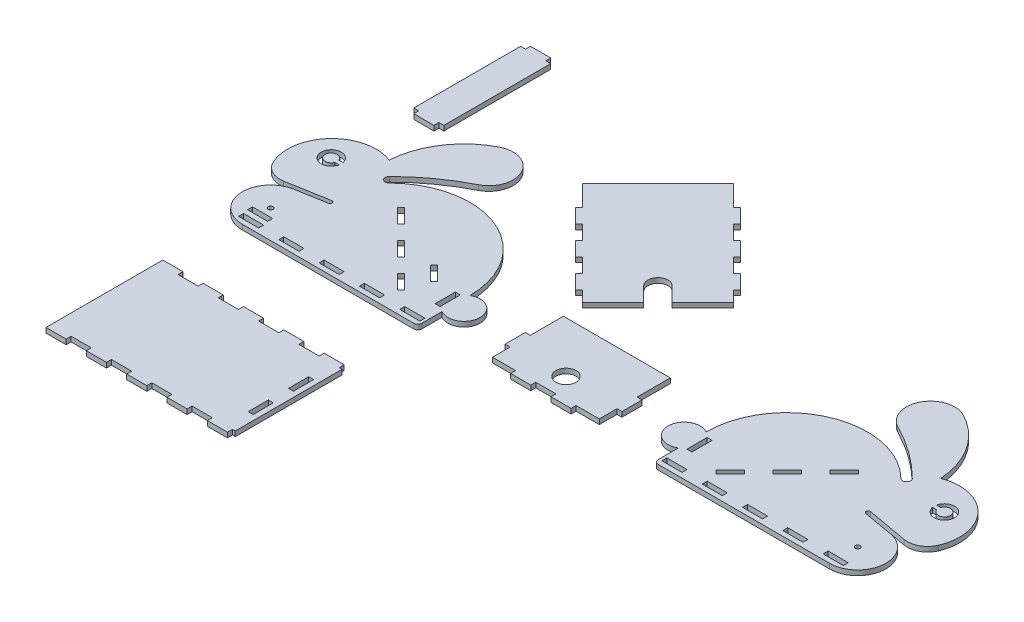
SolidWorks part; units mm, degrees
ref_plane "Front Plane" through (0, 0, 0) normal (0, 0, 1) x (1, 0, 0)
ref_plane "Top Plane" through (0, 0, 0) normal (0, 1, 0) x (1, 0, 0)
ref_plane "Right Plane" through (0, 0, 0) normal (1, 0, 0) x (0, 0, -1)
sketch "Sketch1" plane through (0, 0, 0) normal (0, 1, 0) x (1, 0, 0)
  line L0 (57.15, -63.5) -> (57.15, 63.5) construction
  line L1 (-76.2, 63.5) -> (76.2, 63.5) construction
  line L2 (-76.2, 63.5) -> (-76.2, -63.5) construction
  line L3 (-76.2, -63.5) -> (76.2, -63.5) construction
  line L4 (76.2, 63.5) -> (76.2, -63.5) construction
  line L5 (-76.2, 63.5) -> (76.2, -63.5) construction
  line L6 (-76.2, -63.5) -> (76.2, 63.5) construction
  point P0 (0, 0)
  dimension "D1" = 152.4
  dimension "D2" = 127
  dimension "D3" = 19.05
sketch "Sketch3" plane through (0, 0, 0) normal (0, 1, 0) x (1, 0, 0)
  line L0 (-76.2, -63.5) -> (76.2, -63.5) construction
  line L1 (-76.2, 63.5) -> (-76.2, -63.5) construction
  circle A0 centre (-50.8, -38.1) radius 25.4 construction
  dimension "D1" = 50.8
sketch "Sketch5" plane through (0, 0, 0) normal (0, 1, 0) x (1, 0, 0)
  line L1 (6.35, -55.88) -> (57.15, -55.88) construction
  line L2 (31.75, -55.88) -> (31.75, -63.5) construction
  line L3 (-76.2, -63.5) -> (76.2, -63.5) construction
  line L4 (57.15, -63.5) -> (57.15, 63.5) construction
  arc A0 (6.35, -55.88) -> (57.15, -55.88) centre (31.75, -17.3567) ccw construction
  dimension "D1" = 7.62
  dimension "D2" = 50.8
sketch "Sketch6" plane through (0, 0, 0) normal (0, 1, 0) x (1, 0, 0)
  line L0 (-50.8, -38.1) -> (-50.8, -55.88) construction
  line L1 (-50.8, -55.88) -> (57.15, -55.88) construction
  line L2 (-53.8875, -20.5901) -> (-35.1269, -17.2821) construction
  line L3 (-35.5679, -14.7807) -> (-35.1269, -17.2821) construction
  line L4 (-53.8875, -20.5901) -> (-35.1269, -20.5901) construction
  line L5 (-35.1269, -20.5901) -> (-35.1269, -17.2821) construction
  line L6 (-35.5679, -14.7807) -> (-61.3497, -19.3267) construction
  line L7 (59.69, -53.34) -> (57.15, -53.34) construction
  line L8 (57.15, -53.34) -> (57.15, -55.88) construction
  line L9 (59.69, -53.34) -> (59.69, -40.64) construction
  line L10 (59.69, -40.64) -> (64.77, -31.8412) construction
  line L11 (64.77, -31.8412) -> (59.69, -23.0424) construction
  line L12 (59.69, -23.0424) -> (59.69, -40.64) construction
  line L13 (-27.031, 12.8787) -> (8.89, -23.0424) construction
  line L14 (8.89, -23.0424) -> (59.69, -23.0424) construction
  line L15 (-27.031, 12.8787) -> (-28.8271, 14.6747) construction
  line L16 (-28.8271, 14.6747) -> (-30.6231, 16.4708) construction
  line L17 (-30.6231, 16.4708) -> (-39.6034, 25.451) construction
  line L18 (-11.8373, 67.2263) -> (-4.9647, 53.6239) construction
  line L19 (-4.9647, 53.6239) -> (1.9078, 40.0215) construction
  line L20 (-75.1597, -11.9793) -> (-49.6295, -0.6281) construction
  line L21 (-49.6295, -0.6281) -> (-39.6034, 25.451) construction
  line L22 (-59.0189, 8.2912) -> (-75.1597, -11.9793) construction
  line L23 (-59.0189, 8.2912) -> (-39.6034, 25.451) construction
  line L26 (-55.4268, 9.5612) -> (-52.7972, 9.5612) construction
  line L27 (-55.4268, 7.0212) -> (-52.7972, 7.0212) construction
  line L28 (-52.7972, 9.5612) -> (-52.7972, 7.0212) construction
  line L29 (-55.4268, 9.5612) -> (-55.4268, 7.0212) construction
  arc A0 (-50.8, -55.88) -> (-53.8875, -20.5901) centre (-50.8, -38.1) cw construction
  arc A1 (-35.1269, -17.2821) -> (-35.5679, -14.7807) centre (-35.3474, -16.0314) ccw construction
  arc A2 (57.15, -55.88) -> (59.69, -53.34) centre (57.15, -53.34) ccw construction
  arc A3 (59.69, -40.64) -> (59.69, -23.0424) centre (64.77, -31.8412) ccw construction
  arc A4 (59.69, -23.0424) -> (-27.031, 12.8787) centre (8.89, -23.0424) ccw construction
  arc A5 (-27.031, 12.8787) -> (-30.6231, 16.4708) centre (-28.8271, 14.6747) cw construction
  arc A6 (-30.6231, 16.4708) -> (1.9078, 40.0215) centre (59.1794, -73.3318) cw construction
  arc A7 (1.9078, 40.0215) -> (-11.8373, 67.2263) centre (-4.9647, 53.6239) ccw construction
  arc A8 (-11.8373, 67.2263) -> (-39.6034, 25.451) centre (11.0713, 21.885) ccw construction
  arc A9 (-61.3497, -19.3267) -> (-75.1597, -11.9793) centre (-63.5551, -6.8197) cw construction
  arc A10 (-75.1597, -11.9793) -> (-39.6034, 25.451) centre (-49.6295, -0.6281) cw construction
  arc A11 (-55.4268, 9.5612) -> (-55.4268, 7.0212) centre (-59.0189, 8.2912) ccw construction
  arc A13 (-52.7972, 9.5612) -> (-52.7972, 7.0212) centre (-59.0189, 8.2912) ccw construction
  dimension "D2" = 1.27
  dimension "D3" = 2.54
  dimension "D5" = 10.16
  dimension "D8" = 2.54
  dimension "D11" = 15.24
  dimension "D12" = 127
  dimension "D13" = 50.8
  dimension "D15" = 12.7
  dimension "D16" = 27.94
  dimension "D18" = 7.62
  dimension "D19" = 2.54
  dimension "D1" = 10
  dimension "D4" = 30
  dimension "D6" = 12.7
  dimension "D7" = 135
  dimension "D9" = 180
  dimension "D10" = 50.8
  dimension "D14" = 12.7
  dimension "D17" = 135
  dimension "D20" = 170
  dimension "D21" = 2.54
  dimension "D22" = 19.05
sketch "Sketch7" plane through (0, 0, 0) normal (0, 1, 0) x (1, 0, 0)
  line L0 (-50.8, -55.88) -> (57.15, -55.88) construction
  line L1 (59.69, -53.34) -> (59.69, -40.64) construction
  line L2 (-35.5679, -14.7807) -> (-61.3497, -19.3267) construction
  line L3 (-53.8875, -20.5901) -> (-35.1269, -17.2821) construction
  line L4 (26.1547, -51.1937) -> (0.7547, -51.1937) construction
  line L5 (19.8047, -49.6316) -> (32.5047, -49.6316)
  line L6 (-50.8, -55.88) -> (57.15, -55.88)
  line L7 (59.69, -53.34) -> (59.69, -40.64)
  line L8 (-35.5679, -14.7807) -> (-61.3497, -19.3267)
  line L9 (-53.8875, -20.5901) -> (-35.1269, -17.2821)
  line L10 (-55.4268, 9.5612) -> (-52.7972, 9.5612) construction
  line L11 (-55.4268, 7.0212) -> (-52.7972, 7.0212) construction
  line L12 (-55.4268, 9.5612) -> (-52.7972, 9.5612)
  line L13 (-55.4268, 7.0212) -> (-52.7972, 7.0212)
  line L14 (51.5547, -51.1937) -> (26.1547, -51.1937) construction
  line L15 (45.2047, -49.6316) -> (57.9047, -49.6316)
  line L16 (45.2047, -49.6316) -> (45.2047, -52.7558)
  line L17 (45.2047, -52.7558) -> (57.9047, -52.7558)
  line L18 (57.9047, -49.6316) -> (57.9047, -52.7558)
  line L19 (45.2047, -49.6316) -> (57.9047, -52.7558) construction
  line L20 (45.2047, -52.7558) -> (57.9047, -49.6316) construction
  line L21 (19.8047, -49.6316) -> (19.8047, -52.7558)
  line L22 (19.8047, -52.7558) -> (32.5047, -52.7558)
  line L23 (32.5047, -49.6316) -> (32.5047, -52.7558)
  line L24 (19.8047, -49.6316) -> (32.5047, -52.7558) construction
  line L25 (19.8047, -52.7558) -> (32.5047, -49.6316) construction
  line L26 (0.7547, -51.1937) -> (-24.6453, -51.1937) construction
  line L27 (-5.5953, -49.6316) -> (7.1047, -49.6316)
  line L28 (-5.5953, -49.6316) -> (-5.5953, -52.7558)
  line L29 (-5.5953, -52.7558) -> (7.1047, -52.7558)
  line L30 (7.1047, -49.6316) -> (7.1047, -52.7558)
  line L31 (-5.5953, -49.6316) -> (7.1047, -52.7558) construction
  line L32 (-5.5953, -52.7558) -> (7.1047, -49.6316) construction
  line L33 (-24.6453, -51.1937) -> (-50.0453, -51.1937) construction
  line L34 (-30.9953, -49.6316) -> (-18.2953, -49.6316)
  line L35 (-30.9953, -49.6316) -> (-30.9953, -52.7558)
  line L36 (-30.9953, -52.7558) -> (-18.2953, -52.7558)
  line L37 (-18.2953, -49.6316) -> (-18.2953, -52.7558)
  line L38 (-30.9953, -49.6316) -> (-18.2953, -52.7558) construction
  line L39 (-30.9953, -52.7558) -> (-18.2953, -49.6316) construction
  line L40 (57.9047, -51.1937) -> (54.7805, -51.1937) construction
  line L41 (-56.3953, -49.6316) -> (-43.6953, -49.6316)
  line L42 (-56.3953, -49.6316) -> (-56.3953, -52.7558)
  line L43 (-56.3953, -52.7558) -> (-43.6953, -52.7558)
  line L44 (-43.6953, -49.6316) -> (-43.6953, -52.7558)
  line L45 (-56.3953, -49.6316) -> (-43.6953, -52.7558) construction
  line L46 (-56.3953, -52.7558) -> (-43.6953, -49.6316) construction
  line L47 (54.7805, -51.1937) -> (54.7805, -32.1437) construction
  line L49 (53.2184, -25.7937) -> (56.3426, -25.7937)
  line L50 (53.2184, -25.7937) -> (53.2184, -38.4937)
  line L51 (53.2184, -38.4937) -> (56.3426, -38.4937)
  line L52 (56.3426, -25.7937) -> (56.3426, -38.4937)
  line L53 (53.2184, -25.7937) -> (56.3426, -38.4937) construction
  line L54 (53.2184, -38.4937) -> (56.3426, -25.7937) construction
  arc A0 (-53.8875, -20.5901) -> (-50.8, -55.88) centre (-50.8, -38.1) ccw construction
  arc A1 (57.15, -55.88) -> (59.69, -53.34) centre (57.15, -53.34) ccw construction
  arc A2 (59.69, -40.64) -> (59.69, -23.0424) centre (64.77, -31.8412) ccw construction
  arc A3 (59.69, -23.0424) -> (-27.031, 12.8787) centre (8.89, -23.0424) ccw construction
  arc A4 (-30.6231, 16.4708) -> (-27.031, 12.8787) centre (-28.8271, 14.6747) ccw construction
  arc A5 (1.9078, 40.0215) -> (-30.6231, 16.4708) centre (59.1794, -73.3318) ccw construction
  arc A6 (1.9078, 40.0215) -> (-11.8373, 67.2263) centre (-4.9647, 53.6239) ccw construction
  arc A7 (-11.8373, 67.2263) -> (-39.6034, 25.451) centre (11.0713, 21.885) ccw construction
  arc A8 (-39.6034, 25.451) -> (-75.1597, -11.9793) centre (-49.6295, -0.6281) ccw construction
  arc A9 (-75.1597, -11.9793) -> (-61.3497, -19.3267) centre (-63.5551, -6.8197) ccw construction
  arc A10 (-35.1269, -17.2821) -> (-35.5679, -14.7807) centre (-35.3474, -16.0314) ccw construction
  arc A13 (-53.8875, -20.5901) -> (-50.8, -55.88) centre (-50.8, -38.1) ccw
  arc A14 (57.15, -55.88) -> (59.69, -53.34) centre (57.15, -53.34) ccw
  arc A15 (59.69, -40.64) -> (59.69, -23.0424) centre (64.77, -31.8412) ccw
  arc A16 (59.69, -23.0424) -> (-27.031, 12.8787) centre (8.89, -23.0424) ccw
  arc A17 (-30.6231, 16.4708) -> (-27.031, 12.8787) centre (-28.8271, 14.6747) ccw
  arc A18 (1.9078, 40.0215) -> (-30.6231, 16.4708) centre (59.1794, -73.3318) ccw
  arc A19 (1.9078, 40.0215) -> (-11.8373, 67.2263) centre (-4.9647, 53.6239) ccw
  arc A20 (-11.8373, 67.2263) -> (-39.6034, 25.451) centre (11.0713, 21.885) ccw
  arc A21 (-39.6034, 25.451) -> (-75.1597, -11.9793) centre (-49.6295, -0.6281) ccw
  arc A22 (-75.1597, -11.9793) -> (-61.3497, -19.3267) centre (-63.5551, -6.8197) ccw
  arc A23 (-35.1269, -17.2821) -> (-35.5679, -14.7807) centre (-35.3474, -16.0314) ccw
  arc A24 (-55.4268, 9.5612) -> (-55.4268, 7.0212) centre (-59.0189, 8.2912) ccw construction
  arc A25 (-52.7972, 9.5612) -> (-52.7972, 7.0212) centre (-59.0189, 8.2912) ccw construction
  arc A26 (-55.4268, 9.5612) -> (-55.4268, 7.0212) centre (-59.0189, 8.2912) ccw
  arc A27 (-52.7972, 9.5612) -> (-52.7972, 7.0212) centre (-59.0189, 8.2912) ccw
  point P29 (51.5547, -51.1937)
  dimension "D1" = 3.1242
  dimension "D2" = 12.7
  dimension "D3" = 3.1242
  dimension "D4" = 1.7853
  dimension "D5" = 25.4
  dimension "D6" = 19.05
sketch "Sketch9" plane through (0, 0, 0) normal (0, 1, 0) x (1, 0, 0)
  line L0 (-38.5598, 50.4085) -> (53.2184, -41.3698) construction
  line L1 (-38.5598, 50.4085) -> (-46.8216, 42.1466) construction
  line L2 (53.2184, -41.3698) -> (44.9566, -49.6316) construction
  line L3 (-46.8216, 42.1466) -> (44.9566, -49.6316) construction
  line L4 (-38.5598, 50.4085) -> (44.9566, -49.6316) construction
  line L5 (53.2184, -41.3698) -> (-46.8216, 42.1466) construction
  line L6 (3.1984, 0.3884) -> (3.1984, -55.88) construction
  line L7 (-50.8, -55.88) -> (57.15, -55.88) construction
  line L8 (44.9566, -49.6316) -> (7.2565, -49.6316) construction
  line L9 (19.8047, -49.6316) -> (32.5047, -49.6316) construction
  line L11 (53.2184, -25.7937) -> (53.2184, -38.4937) construction
  point P1 (3.1984, 0.3884)
  dimension "D1" = 129.794
  dimension "D2" = 11.684
  dimension "D3" = 45
sketch "Sketch10" plane through (0, 0, 0) normal (0, 1, 0) x (1, 0, 0)
  line L0 (24.787, -33.8802) -> (33.7672, -42.8605)
  line L1 (24.787, -33.8802) -> (26.9961, -31.6711)
  line L2 (33.7672, -42.8605) -> (35.9764, -40.6513)
  line L3 (26.9961, -31.6711) -> (35.9764, -40.6513)
  line L4 (24.787, -33.8802) -> (35.9764, -40.6513) construction
  line L5 (33.7672, -42.8605) -> (26.9961, -31.6711) construction
  line L6 (45.2047, -49.6316) -> (57.9047, -49.6316) construction
  line L7 (57.9047, -49.6316) -> (57.9047, -52.7558) construction
  line L8 (-46.8216, 42.1466) -> (44.9566, -49.6316) construction
  line L9 (30.3817, -37.2658) -> (12.4211, -19.3053) construction
  line L10 (26.1547, -51.1937) -> (0.7547, -51.1937) construction
  line L11 (9.0356, -13.7106) -> (18.0158, -22.6908)
  line L12 (9.0356, -13.7106) -> (6.8264, -15.9197)
  line L13 (18.0158, -22.6908) -> (15.8067, -24.9)
  line L14 (6.8264, -15.9197) -> (15.8067, -24.9)
  line L15 (9.0356, -13.7106) -> (15.8067, -24.9) construction
  line L16 (18.0158, -22.6908) -> (6.8264, -15.9197) construction
  line L18 (12.4211, -19.3053) -> (-5.5394, -1.3448) construction
  line L19 (-8.9249, 4.2499) -> (0.0553, -4.7303)
  line L20 (-8.9249, 4.2499) -> (-11.1341, 2.0408)
  line L21 (0.0553, -4.7303) -> (-2.1538, -6.9395)
  line L22 (-11.1341, 2.0408) -> (-2.1538, -6.9395)
  line L23 (-8.9249, 4.2499) -> (-2.1538, -6.9395) construction
  line L24 (0.0553, -4.7303) -> (-11.1341, 2.0408) construction
  point P1 (30.3817, -37.2658)
  dimension "D1" = 12.7
sketch "Sketch11" plane through (0, 0, 0) normal (0, 1, 0) x (1, 0, 0)
  line L0 (-30.9953, -49.6316) -> (-18.2953, -49.6316) construction
  line L1 (-35.6617, -24.2316) -> (15.1383, -24.2316) construction
  line L2 (-35.6617, -24.2316) -> (-35.6617, -49.6316) construction
  line L3 (-35.6617, -49.6316) -> (15.1383, -49.6316) construction
  line L4 (15.1383, -24.2316) -> (15.1383, -49.6316) construction
  line L5 (-35.6617, -24.2316) -> (15.1383, -49.6316) construction
  line L6 (-35.6617, -49.6316) -> (15.1383, -24.2316) construction
  line L7 (6.8264, -15.9197) -> (15.8067, -24.9) construction
  point P0 (-10.2617, -36.9316)
  dimension "D1" = 25.4
  dimension "D2" = 50.8
sketch "Sketch12" plane through (0, 0, 0) normal (0, 1, 0) x (1, 0, 0)
  line L0 (59.69, -53.34) -> (59.69, -40.64) construction
  line L1 (56.3426, -25.7937) -> (56.3426, -38.4937) construction
  line L2 (53.2184, -25.7937) -> (56.3426, -25.7937) construction
  line L3 (53.2184, -25.7937) -> (53.2184, -38.4937) construction
  line L4 (53.2184, -38.4937) -> (56.3426, -38.4937) construction
  line L5 (-50.8, -55.88) -> (57.15, -55.88) construction
  line L6 (45.2047, -52.7558) -> (57.9047, -52.7558) construction
  line L7 (57.9047, -49.6316) -> (57.9047, -52.7558) construction
  line L8 (45.2047, -49.6316) -> (57.9047, -49.6316) construction
  line L9 (45.2047, -49.6316) -> (45.2047, -52.7558) construction
  line L10 (19.8047, -49.6316) -> (32.5047, -49.6316) construction
  line L11 (19.8047, -52.7558) -> (32.5047, -52.7558) construction
  line L12 (32.5047, -49.6316) -> (32.5047, -52.7558) construction
  line L13 (19.8047, -49.6316) -> (19.8047, -52.7558) construction
  line L14 (7.1047, -49.6316) -> (7.1047, -52.7558) construction
  line L15 (-5.5953, -49.6316) -> (7.1047, -49.6316) construction
  line L16 (-5.5953, -52.7558) -> (7.1047, -52.7558) construction
  line L17 (-5.5953, -49.6316) -> (-5.5953, -52.7558) construction
  line L18 (-18.2953, -49.6316) -> (-18.2953, -52.7558) construction
  line L19 (-30.9953, -49.6316) -> (-18.2953, -49.6316) construction
  line L20 (-30.9953, -52.7558) -> (-18.2953, -52.7558) construction
  line L21 (-30.9953, -49.6316) -> (-30.9953, -52.7558) construction
  line L22 (-56.3953, -49.6316) -> (-43.6953, -49.6316) construction
  line L23 (-43.6953, -49.6316) -> (-43.6953, -52.7558) construction
  line L24 (-56.3953, -52.7558) -> (-43.6953, -52.7558) construction
  line L25 (-56.3953, -49.6316) -> (-56.3953, -52.7558) construction
  line L26 (-53.8875, -20.5901) -> (-35.1269, -17.2821) construction
  line L27 (-35.5679, -14.7807) -> (-61.3497, -19.3267) construction
  line L28 (-8.9249, 4.2499) -> (-11.1341, 2.0408) construction
  line L29 (-11.1341, 2.0408) -> (-2.1538, -6.9395) construction
  line L30 (0.0553, -4.7303) -> (-2.1538, -6.9395) construction
  line L31 (-8.9249, 4.2499) -> (0.0553, -4.7303) construction
  line L32 (6.8264, -15.9197) -> (15.8067, -24.9) construction
  line L33 (9.0356, -13.7106) -> (6.8264, -15.9197) construction
  line L34 (18.0158, -22.6908) -> (15.8067, -24.9) construction
  line L35 (59.69, -53.34) -> (59.69, -40.64)
  line L36 (56.3426, -25.7937) -> (56.3426, -38.4937)
  line L37 (53.2184, -25.7937) -> (56.3426, -25.7937)
  line L38 (53.2184, -25.7937) -> (53.2184, -38.4937)
  line L39 (53.2184, -38.4937) -> (56.3426, -38.4937)
  line L40 (-50.8, -55.88) -> (57.15, -55.88)
  line L41 (45.2047, -52.7558) -> (57.9047, -52.7558)
  line L42 (57.9047, -49.6316) -> (57.9047, -52.7558)
  line L43 (45.2047, -49.6316) -> (57.9047, -49.6316)
  line L44 (45.2047, -49.6316) -> (45.2047, -52.7558)
  line L45 (19.8047, -49.6316) -> (32.5047, -49.6316)
  line L46 (19.8047, -52.7558) -> (32.5047, -52.7558)
  line L47 (32.5047, -49.6316) -> (32.5047, -52.7558)
  line L48 (19.8047, -49.6316) -> (19.8047, -52.7558)
  line L49 (7.1047, -49.6316) -> (7.1047, -52.7558)
  line L50 (-5.5953, -49.6316) -> (7.1047, -49.6316)
  line L51 (-5.5953, -52.7558) -> (7.1047, -52.7558)
  line L52 (-5.5953, -49.6316) -> (-5.5953, -52.7558)
  line L53 (-18.2953, -49.6316) -> (-18.2953, -52.7558)
  line L54 (-30.9953, -49.6316) -> (-18.2953, -49.6316)
  line L55 (-30.9953, -52.7558) -> (-18.2953, -52.7558)
  line L56 (-30.9953, -49.6316) -> (-30.9953, -52.7558)
  line L57 (-56.3953, -49.6316) -> (-43.6953, -49.6316)
  line L58 (-43.6953, -49.6316) -> (-43.6953, -52.7558)
  line L59 (-56.3953, -52.7558) -> (-43.6953, -52.7558)
  line L60 (-56.3953, -49.6316) -> (-56.3953, -52.7558)
  line L61 (-53.8875, -20.5901) -> (-35.1269, -17.2821)
  line L62 (-35.5679, -14.7807) -> (-61.3497, -19.3267)
  line L63 (-8.9249, 4.2499) -> (-11.1341, 2.0408)
  line L64 (-11.1341, 2.0408) -> (-2.1538, -6.9395)
  line L65 (0.0553, -4.7303) -> (-2.1538, -6.9395)
  line L66 (-8.9249, 4.2499) -> (0.0553, -4.7303)
  line L67 (6.8264, -15.9197) -> (15.8067, -24.9)
  line L68 (9.0356, -13.7106) -> (6.8264, -15.9197)
  line L69 (18.0158, -22.6908) -> (15.8067, -24.9)
  line L70 (9.0356, -13.7106) -> (18.0158, -22.6908) construction
  line L71 (26.9961, -31.6711) -> (35.9764, -40.6513) construction
  line L72 (24.787, -33.8802) -> (26.9961, -31.6711) construction
  line L73 (24.787, -33.8802) -> (33.7672, -42.8605) construction
  line L74 (33.7672, -42.8605) -> (35.9764, -40.6513) construction
  line L75 (9.0356, -13.7106) -> (18.0158, -22.6908)
  line L76 (26.9961, -31.6711) -> (35.9764, -40.6513)
  line L77 (24.787, -33.8802) -> (26.9961, -31.6711)
  line L78 (24.787, -33.8802) -> (33.7672, -42.8605)
  line L79 (33.7672, -42.8605) -> (35.9764, -40.6513)
  line L80 (-55.4268, 9.5612) -> (-52.7972, 9.5612) construction
  line L81 (-55.4268, 7.0212) -> (-52.7972, 7.0212) construction
  line L82 (-55.4268, 9.5612) -> (-52.7972, 9.5612)
  line L83 (-55.4268, 7.0212) -> (-52.7972, 7.0212)
  line L84 (57.9047, -51.1937) -> (134.1047, -51.1937) construction
  line L85 (134.1047, -51.1937) -> (134.1047, -25.7937) construction
  line L86 (323.6363, 7.0212) -> (321.0067, 7.0212)
  line L87 (323.6363, 9.5612) -> (321.0067, 9.5612)
  line L88 (234.4423, -42.8605) -> (232.2331, -40.6513)
  line L89 (243.4225, -33.8802) -> (234.4423, -42.8605)
  line L90 (243.4225, -33.8802) -> (241.2134, -31.6711)
  line L91 (241.2134, -31.6711) -> (232.2331, -40.6513)
  line L92 (259.1739, -13.7106) -> (250.1936, -22.6908)
  line L93 (250.1936, -22.6908) -> (252.4028, -24.9)
  line L94 (259.1739, -13.7106) -> (261.383, -15.9197)
  line L95 (261.383, -15.9197) -> (252.4028, -24.9)
  line L96 (277.1344, 4.2499) -> (268.1542, -4.7303)
  line L97 (268.1542, -4.7303) -> (270.3633, -6.9395)
  line L98 (279.3436, 2.0408) -> (270.3633, -6.9395)
  line L99 (277.1344, 4.2499) -> (279.3436, 2.0408)
  line L100 (303.7774, -14.7807) -> (329.5592, -19.3267)
  line L101 (322.097, -20.5901) -> (303.3364, -17.2821)
  line L102 (324.6047, -49.6316) -> (324.6047, -52.7558)
  line L103 (324.6047, -52.7558) -> (311.9047, -52.7558)
  line L104 (311.9047, -49.6316) -> (311.9047, -52.7558)
  line L105 (324.6047, -49.6316) -> (311.9047, -49.6316)
  line L106 (299.2047, -49.6316) -> (299.2047, -52.7558)
  line L107 (299.2047, -52.7558) -> (286.5047, -52.7558)
  line L108 (299.2047, -49.6316) -> (286.5047, -49.6316)
  line L109 (286.5047, -49.6316) -> (286.5047, -52.7558)
  line L110 (273.8047, -49.6316) -> (273.8047, -52.7558)
  line L111 (273.8047, -52.7558) -> (261.1047, -52.7558)
  line L112 (273.8047, -49.6316) -> (261.1047, -49.6316)
  line L113 (261.1047, -49.6316) -> (261.1047, -52.7558)
  line L114 (248.4047, -49.6316) -> (248.4047, -52.7558)
  line L115 (235.7047, -49.6316) -> (235.7047, -52.7558)
  line L116 (248.4047, -52.7558) -> (235.7047, -52.7558)
  line L117 (248.4047, -49.6316) -> (235.7047, -49.6316)
  line L118 (223.0047, -49.6316) -> (223.0047, -52.7558)
  line L119 (223.0047, -49.6316) -> (210.3047, -49.6316)
  line L120 (210.3047, -49.6316) -> (210.3047, -52.7558)
  line L121 (223.0047, -52.7558) -> (210.3047, -52.7558)
  line L122 (319.0095, -55.88) -> (211.0595, -55.88)
  line L123 (214.991, -38.4937) -> (211.8668, -38.4937)
  line L124 (214.991, -25.7937) -> (214.991, -38.4937)
  line L125 (214.991, -25.7937) -> (211.8668, -25.7937)
  line L126 (211.8668, -25.7937) -> (211.8668, -38.4937)
  line L127 (208.5195, -53.34) -> (208.5195, -40.64)
  line L128 (-50.8, -38.1) -> (-50.8, -44.7421) construction
  line L129 (-57.15, -43.18) -> (-44.45, -43.18)
  line L130 (-57.15, -43.18) -> (-57.15, -46.3042)
  line L131 (-57.15, -46.3042) -> (-44.45, -46.3042)
  line L132 (-44.45, -43.18) -> (-44.45, -46.3042)
  line L133 (-57.15, -43.18) -> (-44.45, -46.3042) construction
  line L134 (-57.15, -46.3042) -> (-44.45, -43.18) construction
  line L136 (-52.6072, 64.4558) -> (39.1711, -27.3224) construction
  line L138 (-38.5598, 50.4085) -> (53.2184, -41.3698) construction
  line L139 (-60.869, 56.194) -> (30.9092, -35.5842) construction
  line L140 (-46.8216, 42.1466) -> (44.9566, -49.6316) construction
  line L141 (30.9092, -35.5842) -> (39.1711, -27.3224) construction
  line L142 (-60.869, 56.194) -> (-52.6072, 64.4558) construction
  line L143 (30.7678, -18.9191) -> (39.7481, -27.8994)
  line L144 (30.7678, -18.9191) -> (32.9769, -16.71)
  line L145 (39.7481, -27.8994) -> (41.9572, -25.6902)
  line L146 (32.9769, -16.71) -> (41.9572, -25.6902)
  line L147 (30.7678, -18.9191) -> (41.9572, -25.6902) construction
  line L148 (39.7481, -27.8994) -> (32.9769, -16.71) construction
  arc A0 (-39.6034, 25.451) -> (-75.1597, -11.9793) centre (-49.6295, -0.6281) ccw construction
  arc A1 (-11.8373, 67.2263) -> (-39.6034, 25.451) centre (11.0713, 21.885) ccw construction
  arc A2 (1.9078, 40.0215) -> (-11.8373, 67.2263) centre (-4.9647, 53.6239) ccw construction
  arc A3 (1.9078, 40.0215) -> (-30.6231, 16.4708) centre (59.1794, -73.3318) ccw construction
  arc A4 (-30.6231, 16.4708) -> (-27.031, 12.8787) centre (-28.8271, 14.6747) ccw construction
  arc A5 (59.69, -23.0424) -> (-27.031, 12.8787) centre (8.89, -23.0424) ccw construction
  arc A6 (59.69, -40.64) -> (59.69, -23.0424) centre (64.77, -31.8412) ccw construction
  arc A7 (57.15, -55.88) -> (59.69, -53.34) centre (57.15, -53.34) ccw construction
  arc A8 (-53.8875, -20.5901) -> (-50.8, -55.88) centre (-50.8, -38.1) ccw construction
  arc A9 (-35.1269, -17.2821) -> (-35.5679, -14.7807) centre (-35.3474, -16.0314) ccw construction
  arc A10 (-75.1597, -11.9793) -> (-61.3497, -19.3267) centre (-63.5551, -6.8197) ccw construction
  arc A11 (-39.6034, 25.451) -> (-75.1597, -11.9793) centre (-49.6295, -0.6281) ccw
  arc A12 (-11.8373, 67.2263) -> (-39.6034, 25.451) centre (11.0713, 21.885) ccw
  arc A13 (1.9078, 40.0215) -> (-11.8373, 67.2263) centre (-4.9647, 53.6239) ccw
  arc A14 (1.9078, 40.0215) -> (-30.6231, 16.4708) centre (59.1794, -73.3318) ccw
  arc A15 (-30.6231, 16.4708) -> (-27.031, 12.8787) centre (-28.8271, 14.6747) ccw
  arc A16 (59.69, -23.0424) -> (-27.031, 12.8787) centre (8.89, -23.0424) ccw
  arc A17 (59.69, -40.64) -> (59.69, -23.0424) centre (64.77, -31.8412) ccw
  arc A18 (57.15, -55.88) -> (59.69, -53.34) centre (57.15, -53.34) ccw
  arc A19 (-53.8875, -20.5901) -> (-50.8, -55.88) centre (-50.8, -38.1) ccw
  arc A20 (-35.1269, -17.2821) -> (-35.5679, -14.7807) centre (-35.3474, -16.0314) ccw
  arc A21 (-75.1597, -11.9793) -> (-61.3497, -19.3267) centre (-63.5551, -6.8197) ccw
  arc A22 (-52.7972, 9.5612) -> (-52.7972, 7.0212) centre (-59.0189, 8.2912) ccw construction
  arc A23 (-55.4268, 9.5612) -> (-55.4268, 7.0212) centre (-59.0189, 8.2912) ccw construction
  arc A24 (-52.7972, 9.5612) -> (-52.7972, 7.0212) centre (-59.0189, 8.2912) ccw
  arc A25 (-55.4268, 9.5612) -> (-55.4268, 7.0212) centre (-59.0189, 8.2912) ccw
  circle A26 centre (-50.8, -38.1) radius 1.524
  circle A27 centre (319.0095, -38.1) radius 1.524
  arc A28 (323.6363, 9.5612) -> (323.6363, 7.0212) centre (327.2284, 8.2912) cw
  arc A29 (321.0067, 9.5612) -> (321.0067, 7.0212) centre (327.2284, 8.2912) cw
  arc A30 (343.3692, -11.9793) -> (329.5592, -19.3267) centre (331.7646, -6.8197) cw
  arc A31 (303.3364, -17.2821) -> (303.7774, -14.7807) centre (303.5569, -16.0314) cw
  arc A32 (322.097, -20.5901) -> (319.0095, -55.88) centre (319.0095, -38.1) cw
  arc A33 (211.0595, -55.88) -> (208.5195, -53.34) centre (211.0595, -53.34) cw
  arc A34 (208.5195, -40.64) -> (208.5195, -23.0424) centre (203.4395, -31.8412) cw
  arc A35 (208.5195, -23.0424) -> (295.2405, 12.8787) centre (259.3195, -23.0424) cw
  arc A36 (298.8326, 16.4708) -> (295.2405, 12.8787) centre (297.0366, 14.6747) cw
  arc A37 (266.3016, 40.0215) -> (298.8326, 16.4708) centre (209.0301, -73.3318) cw
  arc A38 (266.3016, 40.0215) -> (280.0468, 67.2263) centre (273.1742, 53.6239) cw
  arc A39 (280.0468, 67.2263) -> (307.8129, 25.451) centre (257.1382, 21.885) cw
  arc A40 (307.8129, 25.451) -> (343.3692, -11.9793) centre (317.839, -0.6281) cw
  point P58 (26.9961, -31.6711)
  point P142 (-50.8, -44.7421)
  point P157 (36.3625, -22.3047)
  dimension "D1" = 3.048
  dimension "D2" = 76.2
  dimension "D3" = 25.4
  dimension "D4" = 5.08
  dimension "D5" = 19.05
ref_plane "Plane1" through (101.6, 0, 0) normal (1, 0, 0) x (0, 0, -1)
sketch "Sketch13" plane through (0, 0, 0) normal (0, 1, 0) x (1, 0, 0)
  line L0 (-56.3953, -52.7558) -> (-56.3953, -103.5558) construction
  line L1 (59.69, -53.34) -> (59.69, -103.5558) construction
  line L2 (-56.3953, -103.5558) -> (-30.9953, -103.5558) construction
  line L3 (-30.9953, -103.5558) -> (-5.5953, -103.5558) construction
  line L4 (-5.5953, -103.5558) -> (19.8047, -103.5558) construction
  line L5 (19.8047, -103.5558) -> (45.2047, -103.5558) construction
  line L6 (51.5547, -51.1937) -> (26.1547, -51.1937) construction
  line L7 (-56.3953, -103.5558) -> (-56.3953, -100.4316)
  line L8 (53.2184, -118.1608) -> (56.3426, -118.1608)
  line L9 (-56.3953, -100.4316) -> (-43.6953, -100.4316)
  line L10 (-43.6953, -100.4316) -> (-43.6953, -103.5558)
  line L11 (-43.6953, -103.5558) -> (-30.9953, -103.5558)
  line L12 (-30.9953, -103.5558) -> (-30.9953, -100.4316)
  line L13 (53.2184, -118.1608) -> (53.2184, -130.8608)
  line L14 (-30.9953, -100.4316) -> (-18.2953, -100.4316)
  line L15 (-18.2953, -100.4316) -> (-18.2953, -103.5558)
  line L16 (-18.2953, -103.5558) -> (-5.5953, -103.5558)
  line L17 (-5.5953, -103.5558) -> (-5.5953, -100.4316)
  line L18 (-5.5953, -100.4316) -> (7.1047, -100.4316)
  line L19 (7.1047, -100.4316) -> (7.1047, -103.5558)
  line L20 (7.1047, -103.5558) -> (19.8047, -103.5558)
  line L21 (19.8047, -103.5558) -> (19.8047, -100.4316)
  line L22 (19.8047, -100.4316) -> (32.5047, -100.4316)
  line L23 (32.5047, -100.4316) -> (32.5047, -103.5558)
  line L24 (32.5047, -103.5558) -> (45.2047, -103.5558)
  line L25 (45.2047, -103.5558) -> (45.2047, -100.4316)
  line L26 (45.2047, -100.4316) -> (57.9047, -100.4316)
  line L27 (57.9047, -100.4316) -> (57.9047, -103.5558)
  line L28 (57.9047, -49.6316) -> (57.9047, -52.7558) construction
  line L29 (45.2047, -49.6316) -> (57.9047, -49.6316) construction
  line L30 (-56.3953, -103.5558) -> (-56.3953, -170.8658)
  line L31 (-56.3953, -137.2108) -> (57.9047, -137.2108) construction
  line L32 (57.9047, -170.8658) -> (57.9047, -103.5558) construction
  line L33 (19.8047, -170.8658) -> (45.2047, -170.8658) construction
  line L34 (-5.5953, -170.8658) -> (19.8047, -170.8658) construction
  line L35 (-30.9953, -170.8658) -> (-5.5953, -170.8658) construction
  line L36 (-56.3953, -170.8658) -> (-30.9953, -170.8658) construction
  line L37 (57.9047, -173.99) -> (57.9047, -170.8658)
  line L38 (45.2047, -173.99) -> (57.9047, -173.99)
  line L39 (45.2047, -170.8658) -> (45.2047, -173.99)
  line L40 (32.5047, -170.8658) -> (45.2047, -170.8658)
  line L41 (32.5047, -173.99) -> (32.5047, -170.8658)
  line L42 (19.8047, -173.99) -> (32.5047, -173.99)
  line L43 (19.8047, -170.8658) -> (19.8047, -173.99)
  line L44 (7.1047, -170.8658) -> (19.8047, -170.8658)
  line L45 (7.1047, -173.99) -> (7.1047, -170.8658)
  line L46 (-5.5953, -173.99) -> (7.1047, -173.99)
  line L47 (-5.5953, -170.8658) -> (-5.5953, -173.99)
  line L48 (-18.2953, -170.8658) -> (-5.5953, -170.8658)
  line L49 (-18.2953, -173.99) -> (-18.2953, -170.8658)
  line L50 (-30.9953, -173.99) -> (-18.2953, -173.99)
  line L51 (-30.9953, -170.8658) -> (-30.9953, -173.99)
  line L52 (-43.6953, -170.8658) -> (-30.9953, -170.8658)
  line L53 (-43.6953, -173.99) -> (-43.6953, -170.8658)
  line L54 (-56.3953, -173.99) -> (-43.6953, -173.99)
  line L55 (-56.3953, -170.8658) -> (-56.3953, -173.99)
  line L56 (56.3426, -38.4937) -> (56.3426, -173.99) construction
  line L57 (53.2184, -130.8608) -> (56.3426, -130.8608)
  line L58 (56.3426, -118.1608) -> (56.3426, -130.8608)
  line L59 (53.2184, -118.1608) -> (56.3426, -130.8608) construction
  line L60 (53.2184, -130.8608) -> (56.3426, -118.1608) construction
  line L61 (57.9047, -103.5558) -> (59.69, -103.5558)
  line L62 (59.69, -103.5558) -> (59.69, -170.8658)
  line L63 (57.9047, -170.8658) -> (59.69, -170.8658)
  line L64 (53.2184, -143.5608) -> (56.3426, -156.2608) construction
  line L65 (53.2184, -156.2608) -> (56.3426, -143.5608) construction
  line L66 (56.3426, -156.2608) -> (56.3426, -143.5608)
  line L67 (53.2184, -143.5608) -> (56.3426, -143.5608)
  line L68 (53.2184, -156.2608) -> (53.2184, -143.5608)
  line L69 (53.2184, -156.2608) -> (56.3426, -156.2608)
  point P2 (54.7805, -124.5108)
  point P63 (59.69, -137.2108)
  point P67 (54.7805, -149.9108)
  dimension "D1" = 50.8
  dimension "D2" = 67.31
  dimension "D3" = 25.4
sketch "Sketch14" plane through (0, 0, 0) normal (0, 1, 0) x (1, 0, 0)
  line L0 (56.3426, -25.7937) -> (97.3255, -25.7937) construction
  line L1 (97.3255, -25.7937) -> (97.3255, -38.4937)
  line L2 (56.3426, -25.7937) -> (56.3426, -38.4937) construction
  line L3 (97.3255, -25.7937) -> (100.4497, -25.7937)
  line L4 (97.3255, -38.4937) -> (100.4497, -38.4937)
  line L5 (57.9047, -49.6316) -> (57.9047, -52.7558) construction
  line L6 (57.9047, -49.6316) -> (100.4497, -49.6316) construction
  line L7 (100.4497, -38.4937) -> (100.4497, -49.6316)
  line L8 (56.3426, -25.7937) -> (56.3426, -4.9071) construction
  line L9 (56.3426, -4.9071) -> (100.4497, -4.9071) construction
  line L10 (100.4497, -4.9071) -> (100.4497, -25.7937)
  line L11 (100.4497, -49.6316) -> (115.0547, -49.6316)
  line L12 (134.1047, -51.1937) -> (134.1047, -25.7937) construction
  line L13 (100.4497, -4.9071) -> (167.7597, -4.9071)
  line L14 (134.1047, -4.9071) -> (134.1047, -49.6316) construction
  line L15 (167.7597, -4.9071) -> (167.7597, -25.7937)
  line L16 (167.7597, -38.4937) -> (167.7597, -49.6316)
  line L17 (170.8839, -38.4937) -> (167.7597, -38.4937)
  line L18 (170.8839, -25.7937) -> (167.7597, -25.7937)
  line L19 (170.8839, -25.7937) -> (170.8839, -38.4937)
  line L20 (45.2047, -49.6316) -> (57.9047, -49.6316) construction
  line L21 (115.0547, -49.6316) -> (127.7547, -49.6316) construction
  line L22 (115.0547, -49.6316) -> (115.0547, -52.7558)
  line L23 (115.0547, -52.7558) -> (127.7547, -52.7558)
  line L24 (127.7547, -49.6316) -> (127.7547, -52.7558)
  line L25 (115.0547, -49.6316) -> (127.7547, -52.7558) construction
  line L26 (115.0547, -52.7558) -> (127.7547, -49.6316) construction
  line L27 (127.7547, -49.6316) -> (140.4547, -49.6316)
  line L28 (153.1547, -52.7558) -> (140.4547, -49.6316) construction
  line L29 (153.1547, -49.6316) -> (140.4547, -52.7558) construction
  line L30 (153.1547, -49.6316) -> (140.4547, -49.6316) construction
  line L31 (140.4547, -49.6316) -> (140.4547, -52.7558)
  line L32 (153.1547, -52.7558) -> (140.4547, -52.7558)
  line L33 (153.1547, -49.6316) -> (153.1547, -52.7558)
  line L34 (167.7597, -49.6316) -> (153.1547, -49.6316)
  arc A0 (59.69, -23.0424) -> (-27.031, 12.8787) centre (8.89, -23.0424) ccw construction
  circle A1 centre (134.1047, -36.9316) radius 6.35
  point P28 (121.4047, -51.1937)
  point P39 (146.8047, -51.1937)
  dimension "D3" = 12.7
  dimension "D1" = 67.31
  dimension "D2" = 25.4
  dimension "D4" = 12.7
sketch "Sketch15" plane through (0, 0, 0) normal (0, 1, 0) x (1, 0, 0)
  line L0 (-8.9249, 4.2499) -> (44.9566, 58.1315) construction
  line L1 (-8.9249, 4.2499) -> (-11.1341, 2.0408) construction
  line L2 (44.9566, 58.1315) -> (53.9369, 49.1512)
  line L3 (53.9369, 49.1512) -> (56.146, 51.3604)
  line L4 (56.146, 51.3604) -> (65.1263, 42.3801)
  line L5 (65.1263, 42.3801) -> (62.9171, 40.171)
  line L6 (62.9171, 40.171) -> (71.8974, 31.1907)
  line L7 (71.8974, 31.1907) -> (74.1065, 33.3998)
  line L8 (74.1065, 33.3998) -> (83.0868, 24.4196)
  line L9 (83.0868, 24.4196) -> (80.8776, 22.2104)
  line L10 (80.8776, 22.2104) -> (89.8579, 13.2302)
  line L11 (89.8579, 13.2302) -> (92.067, 15.4393)
  line L12 (-11.1341, 2.0408) -> (-2.1538, -6.9395) construction
  line L13 (44.9566, 58.1315) -> (47.1658, 60.3406)
  line L14 (47.1658, 60.3406) -> (34.1123, 73.3941)
  line L15 (47.1658, 60.3406) -> (65.1263, 42.3801) construction
  line L16 (65.1263, 42.3801) -> (83.0868, 24.4196) construction
  line L17 (51.5547, -51.1937) -> (26.1547, -51.1937) construction
  line L18 (34.1123, 73.3941) -> (-21.9784, 17.3034) construction
  line L19 (-8.9249, 4.2499) -> (-21.9784, 17.3034) construction
  line L20 (45.2047, -49.6316) -> (32.5047, -49.6316) construction
  line L21 (33.7672, -42.8605) -> (40.5383, -49.6316) construction
  line L22 (24.787, -33.8802) -> (33.7672, -42.8605) construction
  line L23 (40.5383, -49.6316) -> (98.8381, 8.6682) construction
  line L24 (92.067, 15.4393) -> (98.8381, 8.6682)
  line L25 (34.1123, 73.3941) -> (81.7076, 120.9894)
  line L26 (57.91, 97.1918) -> (122.6358, 32.4659) construction
  line L27 (146.4335, 56.2636) -> (127.126, 36.956)
  line L28 (109.1654, 36.956) -> (118.1457, 27.9758)
  line L29 (112.7216, 89.9755) -> (130.6821, 72.0149) construction
  line L30 (94.7611, 107.936) -> (112.7216, 89.9755) construction
  line L31 (118.1457, 45.9363) -> (127.126, 36.956)
  line L32 (139.6624, 63.0347) -> (146.4335, 56.2636)
  line L33 (94.7611, 107.936) -> (81.7076, 120.9894)
  line L34 (96.9703, 110.1451) -> (94.7611, 107.936)
  line L35 (141.8715, 65.2438) -> (139.6624, 63.0347)
  line L36 (132.8913, 74.2241) -> (141.8715, 65.2438)
  line L37 (130.6821, 72.0149) -> (132.8913, 74.2241)
  line L38 (121.7019, 80.9952) -> (130.6821, 72.0149)
  line L39 (123.911, 83.2043) -> (121.7019, 80.9952)
  line L40 (114.9308, 92.1846) -> (123.911, 83.2043)
  line L41 (112.7216, 89.9755) -> (114.9308, 92.1846)
  line L42 (103.7414, 98.9557) -> (112.7216, 89.9755)
  line L43 (105.9505, 101.1649) -> (103.7414, 98.9557)
  line L44 (96.9703, 110.1451) -> (105.9505, 101.1649)
  line L45 (118.1457, 27.9758) -> (98.8381, 8.6682)
  line L46 (118.1457, 27.9758) -> (122.6358, 32.4659) construction
  line L47 (122.6358, 32.4659) -> (127.126, 36.956) construction
  arc A0 (59.69, -23.0424) -> (-27.031, 12.8787) centre (8.89, -23.0424) ccw construction
  arc A1 (118.1457, 45.9363) -> (109.1654, 36.956) centre (113.6556, 41.4462) ccw
  dimension "D3" = 12.7
  dimension "D1" = 76.2
  dimension "D2" = 67.31
  dimension "D4" = 12.7
sketch "Sketch17" plane through (0, 0, 0) normal (0, 1, 0) x (1, 0, 0)
  line L0 (-57.15, -43.18) -> (-57.15, 58.42) construction
  line L1 (-44.45, -43.18) -> (-44.45, 58.42) construction
  line L2 (-57.15, 58.42) -> (-44.45, 58.42)
  line L3 (-57.15, 58.42) -> (-57.15, 61.5442)
  line L4 (-57.15, 61.5442) -> (-60.2742, 61.5442)
  line L5 (-60.2742, 61.5442) -> (-60.2742, 128.8542)
  line L6 (-60.2742, 95.1992) -> (-41.3258, 95.1992) construction
  line L7 (-41.3258, 128.8542) -> (-41.3258, 61.5442)
  line L8 (-41.3258, 61.5442) -> (-44.45, 61.5442)
  line L9 (-44.45, 61.5442) -> (-44.45, 58.42)
  line L11 (57.9047, -49.6316) -> (57.9047, -52.7558) construction
  line L12 (-44.45, 128.8542) -> (-44.45, 131.9784)
  line L13 (-41.3258, 128.8542) -> (-44.45, 128.8542)
  line L14 (-57.15, 128.8542) -> (-60.2742, 128.8542)
  line L15 (-57.15, 131.9784) -> (-57.15, 128.8542)
  line L16 (-57.15, 131.9784) -> (-44.45, 131.9784)
  dimension "D1" = 67.31
  dimension "D2" = 101.6
sketch "Sketch16" plane through (0, 0, 0) normal (0, 1, 0) x (1, 0, 0)
  line L0 (-57.15, -43.18) -> (-44.45, -43.18) construction
  line L1 (-44.45, -43.18) -> (-44.45, -46.3042) construction
  line L2 (-55.4268, 9.5612) -> (-52.7972, 9.5612)
  line L3 (-52.7972, 7.0212) -> (-55.4268, 7.0212)
  line L4 (32.5047, -49.6316) -> (19.8047, -49.6316)
  line L5 (32.5047, -52.7558) -> (32.5047, -49.6316)
  line L6 (19.8047, -52.7558) -> (32.5047, -52.7558)
  line L7 (19.8047, -49.6316) -> (19.8047, -52.7558)
  line L8 (32.5047, -49.6316) -> (19.8047, -49.6316)
  line L9 (32.5047, -52.7558) -> (32.5047, -49.6316)
  line L10 (19.8047, -52.7558) -> (32.5047, -52.7558)
  line L11 (19.8047, -49.6316) -> (19.8047, -52.7558)
  line L12 (45.2047, -52.7558) -> (57.9047, -52.7558)
  line L13 (57.9047, -52.7558) -> (57.9047, -49.6316)
  line L14 (57.9047, -49.6316) -> (45.2047, -49.6316)
  line L15 (45.2047, -49.6316) -> (45.2047, -52.7558)
  line L16 (45.2047, -52.7558) -> (57.9047, -52.7558)
  line L17 (57.9047, -52.7558) -> (57.9047, -49.6316)
  line L18 (57.9047, -49.6316) -> (45.2047, -49.6316)
  line L19 (45.2047, -49.6316) -> (45.2047, -52.7558)
  line L20 (56.3426, -38.4937) -> (56.3426, -25.7937)
  line L21 (53.2184, -38.4937) -> (56.3426, -38.4937)
  line L22 (53.2184, -25.7937) -> (53.2184, -38.4937)
  line L23 (56.3426, -25.7937) -> (53.2184, -25.7937)
  line L24 (56.3426, -38.4937) -> (56.3426, -25.7937)
  line L25 (53.2184, -38.4937) -> (56.3426, -38.4937)
  line L26 (53.2184, -25.7937) -> (53.2184, -38.4937)
  line L27 (56.3426, -25.7937) -> (53.2184, -25.7937)
  line L28 (-43.6953, -49.6316) -> (-56.3953, -49.6316)
  line L29 (-43.6953, -52.7558) -> (-43.6953, -49.6316)
  line L30 (-56.3953, -52.7558) -> (-43.6953, -52.7558)
  line L31 (-56.3953, -49.6316) -> (-56.3953, -52.7558)
  line L32 (-43.6953, -49.6316) -> (-56.3953, -49.6316)
  line L33 (-43.6953, -52.7558) -> (-43.6953, -49.6316)
  line L34 (-56.3953, -52.7558) -> (-43.6953, -52.7558)
  line L35 (-56.3953, -49.6316) -> (-56.3953, -52.7558)
  line L36 (-18.2953, -52.7558) -> (-18.2953, -49.6316)
  line L37 (-30.9953, -52.7558) -> (-18.2953, -52.7558)
  line L38 (-30.9953, -49.6316) -> (-30.9953, -52.7558)
  line L39 (-18.2953, -49.6316) -> (-30.9953, -49.6316)
  line L40 (-18.2953, -52.7558) -> (-18.2953, -49.6316)
  line L41 (-30.9953, -52.7558) -> (-18.2953, -52.7558)
  line L42 (-30.9953, -49.6316) -> (-30.9953, -52.7558)
  line L43 (-18.2953, -49.6316) -> (-30.9953, -49.6316)
  line L44 (7.1047, -52.7558) -> (7.1047, -49.6316)
  line L45 (7.1047, -49.6316) -> (-5.5953, -49.6316)
  line L46 (-5.5953, -49.6316) -> (-5.5953, -52.7558)
  line L47 (-5.5953, -52.7558) -> (7.1047, -52.7558)
  line L48 (7.1047, -52.7558) -> (7.1047, -49.6316)
  line L49 (7.1047, -49.6316) -> (-5.5953, -49.6316)
  line L50 (-5.5953, -49.6316) -> (-5.5953, -52.7558)
  line L51 (-5.5953, -52.7558) -> (7.1047, -52.7558)
  line L52 (6.8264, -15.9197) -> (15.8067, -24.9)
  line L53 (15.8067, -24.9) -> (18.0158, -22.6908)
  line L54 (18.0158, -22.6908) -> (9.0356, -13.7106)
  line L55 (9.0356, -13.7106) -> (6.8264, -15.9197)
  line L56 (6.8264, -15.9197) -> (15.8067, -24.9)
  line L57 (15.8067, -24.9) -> (18.0158, -22.6908)
  line L58 (18.0158, -22.6908) -> (9.0356, -13.7106)
  line L59 (9.0356, -13.7106) -> (6.8264, -15.9197)
  line L60 (-8.9249, 4.2499) -> (-11.1341, 2.0408)
  line L61 (-11.1341, 2.0408) -> (-2.1538, -6.9395)
  line L62 (-2.1538, -6.9395) -> (0.0553, -4.7303)
  line L63 (0.0553, -4.7303) -> (-8.9249, 4.2499)
  line L64 (-8.9249, 4.2499) -> (-11.1341, 2.0408)
  line L65 (-11.1341, 2.0408) -> (-2.1538, -6.9395)
  line L66 (-2.1538, -6.9395) -> (0.0553, -4.7303)
  line L67 (0.0553, -4.7303) -> (-8.9249, 4.2499)
  line L68 (-61.3497, -19.3267) -> (-35.5679, -14.7807)
  line L69 (59.69, -53.34) -> (59.69, -40.64)
  line L70 (-50.8, -55.88) -> (57.15, -55.88)
  line L71 (-35.1269, -17.2821) -> (-53.8875, -20.5901)
  line L72 (-61.3497, -19.3267) -> (-35.5679, -14.7807)
  line L73 (59.69, -53.34) -> (59.69, -40.64)
  line L74 (-50.8, -55.88) -> (57.15, -55.88)
  line L75 (-35.1269, -17.2821) -> (-53.8875, -20.5901)
  line L76 (-55.4268, 9.5612) -> (-52.7972, 9.5612)
  line L77 (-52.7972, 7.0212) -> (-55.4268, 7.0212)
  line L78 (323.6363, 7.0212) -> (321.0067, 7.0212)
  line L79 (321.0067, 9.5612) -> (323.6363, 9.5612)
  line L80 (33.7672, -42.8605) -> (35.9764, -40.6513)
  line L81 (35.9764, -40.6513) -> (26.9961, -31.6711)
  line L82 (26.9961, -31.6711) -> (24.787, -33.8802)
  line L83 (24.787, -33.8802) -> (33.7672, -42.8605)
  line L84 (33.7672, -42.8605) -> (35.9764, -40.6513)
  line L85 (35.9764, -40.6513) -> (26.9961, -31.6711)
  line L86 (26.9961, -31.6711) -> (24.787, -33.8802)
  line L87 (24.787, -33.8802) -> (33.7672, -42.8605)
  line L88 (323.6363, 7.0212) -> (321.0067, 7.0212)
  line L89 (321.0067, 9.5612) -> (323.6363, 9.5612)
  line L90 (-57.15, -46.3042) -> (-44.45, -46.3042) construction
  line L91 (-57.15, -43.18) -> (-57.15, -46.3042) construction
  line L92 (303.7774, -14.7807) -> (329.5592, -19.3267)
  line L93 (322.097, -20.5901) -> (303.3364, -17.2821)
  line L94 (211.0595, -55.88) -> (319.0095, -55.88)
  line L95 (208.5195, -40.64) -> (208.5195, -53.34)
  line L96 (303.7774, -14.7807) -> (329.5592, -19.3267)
  line L97 (322.097, -20.5901) -> (303.3364, -17.2821)
  line L98 (211.0595, -55.88) -> (319.0095, -55.88)
  line L99 (208.5195, -40.64) -> (208.5195, -53.34)
  line L100 (232.2331, -40.6513) -> (234.4423, -42.8605)
  line L101 (241.2134, -31.6711) -> (232.2331, -40.6513)
  line L102 (243.4225, -33.8802) -> (241.2134, -31.6711)
  line L103 (234.4423, -42.8605) -> (243.4225, -33.8802)
  line L104 (232.2331, -40.6513) -> (234.4423, -42.8605)
  line L105 (241.2134, -31.6711) -> (232.2331, -40.6513)
  line L106 (243.4225, -33.8802) -> (241.2134, -31.6711)
  line L107 (234.4423, -42.8605) -> (243.4225, -33.8802)
  line L108 (299.2047, -52.7558) -> (299.2047, -49.6316)
  line L109 (286.5047, -52.7558) -> (299.2047, -52.7558)
  line L110 (286.5047, -49.6316) -> (286.5047, -52.7558)
  line L111 (299.2047, -49.6316) -> (286.5047, -49.6316)
  line L112 (299.2047, -52.7558) -> (299.2047, -49.6316)
  line L113 (286.5047, -52.7558) -> (299.2047, -52.7558)
  line L114 (286.5047, -49.6316) -> (286.5047, -52.7558)
  line L115 (299.2047, -49.6316) -> (286.5047, -49.6316)
  line L116 (324.6047, -52.7558) -> (324.6047, -49.6316)
  line L117 (311.9047, -52.7558) -> (324.6047, -52.7558)
  line L118 (311.9047, -49.6316) -> (311.9047, -52.7558)
  line L119 (324.6047, -49.6316) -> (311.9047, -49.6316)
  line L120 (324.6047, -52.7558) -> (324.6047, -49.6316)
  line L121 (311.9047, -52.7558) -> (324.6047, -52.7558)
  line L122 (311.9047, -49.6316) -> (311.9047, -52.7558)
  line L123 (324.6047, -49.6316) -> (311.9047, -49.6316)
  line L124 (277.1344, 4.2499) -> (268.1542, -4.7303)
  line L125 (268.1542, -4.7303) -> (270.3633, -6.9395)
  line L126 (270.3633, -6.9395) -> (279.3436, 2.0408)
  line L127 (279.3436, 2.0408) -> (277.1344, 4.2499)
  line L128 (277.1344, 4.2499) -> (268.1542, -4.7303)
  line L129 (268.1542, -4.7303) -> (270.3633, -6.9395)
  line L130 (270.3633, -6.9395) -> (279.3436, 2.0408)
  line L131 (279.3436, 2.0408) -> (277.1344, 4.2499)
  line L132 (250.1936, -22.6908) -> (252.4028, -24.9)
  line L133 (259.1739, -13.7106) -> (250.1936, -22.6908)
  line L134 (261.383, -15.9197) -> (259.1739, -13.7106)
  line L135 (252.4028, -24.9) -> (261.383, -15.9197)
  line L136 (250.1936, -22.6908) -> (252.4028, -24.9)
  line L137 (259.1739, -13.7106) -> (250.1936, -22.6908)
  line L138 (261.383, -15.9197) -> (259.1739, -13.7106)
  line L139 (252.4028, -24.9) -> (261.383, -15.9197)
  line L140 (211.8668, -38.4937) -> (214.991, -38.4937)
  line L141 (211.8668, -25.7937) -> (211.8668, -38.4937)
  line L142 (214.991, -25.7937) -> (211.8668, -25.7937)
  line L143 (214.991, -38.4937) -> (214.991, -25.7937)
  line L144 (211.8668, -38.4937) -> (214.991, -38.4937)
  line L145 (211.8668, -25.7937) -> (211.8668, -38.4937)
  line L146 (214.991, -25.7937) -> (211.8668, -25.7937)
  line L147 (214.991, -38.4937) -> (214.991, -25.7937)
  line L148 (223.0047, -52.7558) -> (223.0047, -49.6316)
  line L149 (210.3047, -52.7558) -> (223.0047, -52.7558)
  line L150 (210.3047, -49.6316) -> (210.3047, -52.7558)
  line L151 (223.0047, -49.6316) -> (210.3047, -49.6316)
  line L152 (223.0047, -52.7558) -> (223.0047, -49.6316)
  line L153 (210.3047, -52.7558) -> (223.0047, -52.7558)
  line L154 (210.3047, -49.6316) -> (210.3047, -52.7558)
  line L155 (223.0047, -49.6316) -> (210.3047, -49.6316)
  line L156 (248.4047, -52.7558) -> (248.4047, -49.6316)
  line L157 (235.7047, -52.7558) -> (248.4047, -52.7558)
  line L158 (235.7047, -49.6316) -> (235.7047, -52.7558)
  line L159 (248.4047, -49.6316) -> (235.7047, -49.6316)
  line L160 (248.4047, -52.7558) -> (248.4047, -49.6316)
  line L161 (235.7047, -52.7558) -> (248.4047, -52.7558)
  line L162 (235.7047, -49.6316) -> (235.7047, -52.7558)
  line L163 (248.4047, -49.6316) -> (235.7047, -49.6316)
  line L164 (261.1047, -52.7558) -> (273.8047, -52.7558)
  line L165 (273.8047, -52.7558) -> (273.8047, -49.6316)
  line L166 (273.8047, -49.6316) -> (261.1047, -49.6316)
  line L167 (261.1047, -49.6316) -> (261.1047, -52.7558)
  line L168 (261.1047, -52.7558) -> (273.8047, -52.7558)
  line L169 (273.8047, -52.7558) -> (273.8047, -49.6316)
  line L170 (273.8047, -49.6316) -> (261.1047, -49.6316)
  line L171 (261.1047, -49.6316) -> (261.1047, -52.7558)
  line L172 (56.3426, -118.1608) -> (53.2184, -118.1608)
  line L173 (56.3426, -130.8608) -> (56.3426, -118.1608)
  line L174 (53.2184, -130.8608) -> (56.3426, -130.8608)
  line L175 (53.2184, -118.1608) -> (53.2184, -130.8608)
  line L176 (56.3426, -118.1608) -> (53.2184, -118.1608)
  line L177 (56.3426, -130.8608) -> (56.3426, -118.1608)
  line L178 (53.2184, -130.8608) -> (56.3426, -130.8608)
  line L179 (53.2184, -118.1608) -> (53.2184, -130.8608)
  line L180 (56.3426, -156.2608) -> (56.3426, -143.5608)
  line L181 (56.3426, -143.5608) -> (53.2184, -143.5608)
  line L182 (53.2184, -143.5608) -> (53.2184, -156.2608)
  line L183 (53.2184, -156.2608) -> (56.3426, -156.2608)
  line L184 (56.3426, -156.2608) -> (56.3426, -143.5608)
  line L185 (56.3426, -143.5608) -> (53.2184, -143.5608)
  line L186 (53.2184, -143.5608) -> (53.2184, -156.2608)
  line L187 (53.2184, -156.2608) -> (56.3426, -156.2608)
  line L188 (-57.15, -43.18) -> (-44.45, -43.18)
  line L189 (-44.45, -43.18) -> (-44.45, -46.3042)
  line L190 (-57.15, -46.3042) -> (-44.45, -46.3042)
  line L191 (-57.15, -43.18) -> (-57.15, -46.3042)
  line L192 (30.7678, -18.9191) -> (32.9769, -16.71) construction
  line L193 (32.9769, -16.71) -> (41.9572, -25.6902) construction
  line L194 (39.7481, -27.8994) -> (41.9572, -25.6902) construction
  line L195 (30.7678, -18.9191) -> (39.7481, -27.8994) construction
  line L196 (30.7678, -18.9191) -> (32.9769, -16.71)
  line L197 (32.9769, -16.71) -> (41.9572, -25.6902)
  line L198 (39.7481, -27.8994) -> (41.9572, -25.6902)
  line L199 (30.7678, -18.9191) -> (39.7481, -27.8994)
  line L204 (127.7547, -49.6316) -> (140.4547, -49.6316)
  line L205 (140.4547, -49.6316) -> (140.4547, -52.7558)
  line L206 (140.4547, -52.7558) -> (153.1547, -52.7558)
  line L207 (153.1547, -52.7558) -> (153.1547, -49.6316)
  line L208 (153.1547, -49.6316) -> (167.7597, -49.6316)
  line L209 (167.7597, -49.6316) -> (167.7597, -38.4937)
  line L210 (-43.6953, -173.99) -> (-43.6953, -170.8658)
  line L211 (-56.3953, -173.99) -> (-43.6953, -173.99)
  line L212 (-56.3953, -170.8658) -> (-56.3953, -173.99)
  line L213 (-56.3953, -103.5558) -> (-56.3953, -170.8658)
  line L214 (-56.3953, -100.4316) -> (-56.3953, -103.5558)
  line L215 (-43.6953, -100.4316) -> (-56.3953, -100.4316)
  line L216 (-43.6953, -103.5558) -> (-43.6953, -100.4316)
  line L217 (-30.9953, -103.5558) -> (-43.6953, -103.5558)
  line L218 (-30.9953, -100.4316) -> (-30.9953, -103.5558)
  line L219 (-18.2953, -100.4316) -> (-30.9953, -100.4316)
  line L220 (-18.2953, -103.5558) -> (-18.2953, -100.4316)
  line L221 (-5.5953, -103.5558) -> (-18.2953, -103.5558)
  line L222 (-5.5953, -100.4316) -> (-5.5953, -103.5558)
  line L223 (7.1047, -100.4316) -> (-5.5953, -100.4316)
  line L224 (7.1047, -103.5558) -> (7.1047, -100.4316)
  line L225 (19.8047, -103.5558) -> (7.1047, -103.5558)
  line L226 (19.8047, -100.4316) -> (19.8047, -103.5558)
  line L227 (32.5047, -100.4316) -> (19.8047, -100.4316)
  line L228 (32.5047, -103.5558) -> (32.5047, -100.4316)
  line L229 (45.2047, -103.5558) -> (32.5047, -103.5558)
  line L230 (45.2047, -100.4316) -> (45.2047, -103.5558)
  line L231 (57.9047, -100.4316) -> (45.2047, -100.4316)
  line L232 (57.9047, -103.5558) -> (57.9047, -100.4316)
  line L233 (59.69, -103.5558) -> (57.9047, -103.5558)
  line L234 (59.69, -170.8658) -> (59.69, -103.5558)
  line L235 (57.9047, -170.8658) -> (59.69, -170.8658)
  line L236 (57.9047, -173.99) -> (57.9047, -170.8658)
  line L237 (45.2047, -173.99) -> (57.9047, -173.99)
  line L238 (45.2047, -170.8658) -> (45.2047, -173.99)
  line L239 (32.5047, -170.8658) -> (45.2047, -170.8658)
  line L240 (32.5047, -173.99) -> (32.5047, -170.8658)
  line L241 (19.8047, -173.99) -> (32.5047, -173.99)
  line L242 (19.8047, -170.8658) -> (19.8047, -173.99)
  line L243 (7.1047, -170.8658) -> (19.8047, -170.8658)
  line L244 (7.1047, -173.99) -> (7.1047, -170.8658)
  line L245 (-5.5953, -173.99) -> (7.1047, -173.99)
  line L246 (-5.5953, -170.8658) -> (-5.5953, -173.99)
  line L247 (-18.2953, -170.8658) -> (-5.5953, -170.8658)
  line L248 (-18.2953, -173.99) -> (-18.2953, -170.8658)
  line L249 (-30.9953, -173.99) -> (-18.2953, -173.99)
  line L250 (-30.9953, -170.8658) -> (-30.9953, -173.99)
  line L251 (-43.6953, -170.8658) -> (-30.9953, -170.8658)
  line L252 (-43.6953, -173.99) -> (-43.6953, -170.8658)
  line L253 (-56.3953, -173.99) -> (-43.6953, -173.99)
  line L254 (-56.3953, -170.8658) -> (-56.3953, -173.99)
  line L255 (-56.3953, -103.5558) -> (-56.3953, -170.8658)
  line L256 (-56.3953, -100.4316) -> (-56.3953, -103.5558)
  line L257 (-43.6953, -100.4316) -> (-56.3953, -100.4316)
  line L258 (-43.6953, -103.5558) -> (-43.6953, -100.4316)
  line L259 (-30.9953, -103.5558) -> (-43.6953, -103.5558)
  line L260 (-30.9953, -100.4316) -> (-30.9953, -103.5558)
  line L261 (-18.2953, -100.4316) -> (-30.9953, -100.4316)
  line L262 (-18.2953, -103.5558) -> (-18.2953, -100.4316)
  line L263 (-5.5953, -103.5558) -> (-18.2953, -103.5558)
  line L264 (-5.5953, -100.4316) -> (-5.5953, -103.5558)
  line L265 (7.1047, -100.4316) -> (-5.5953, -100.4316)
  line L266 (7.1047, -103.5558) -> (7.1047, -100.4316)
  line L267 (19.8047, -103.5558) -> (7.1047, -103.5558)
  line L268 (19.8047, -100.4316) -> (19.8047, -103.5558)
  line L269 (32.5047, -100.4316) -> (19.8047, -100.4316)
  line L270 (32.5047, -103.5558) -> (32.5047, -100.4316)
  line L271 (45.2047, -103.5558) -> (32.5047, -103.5558)
  line L272 (45.2047, -100.4316) -> (45.2047, -103.5558)
  line L273 (57.9047, -100.4316) -> (45.2047, -100.4316)
  line L274 (57.9047, -103.5558) -> (57.9047, -100.4316)
  line L275 (59.69, -103.5558) -> (57.9047, -103.5558)
  line L276 (59.69, -170.8658) -> (59.69, -103.5558)
  line L277 (57.9047, -170.8658) -> (59.69, -170.8658)
  line L278 (57.9047, -173.99) -> (57.9047, -170.8658)
  line L279 (45.2047, -173.99) -> (57.9047, -173.99)
  line L280 (45.2047, -170.8658) -> (45.2047, -173.99)
  line L281 (32.5047, -170.8658) -> (45.2047, -170.8658)
  line L282 (32.5047, -173.99) -> (32.5047, -170.8658)
  line L283 (19.8047, -173.99) -> (32.5047, -173.99)
  line L284 (19.8047, -170.8658) -> (19.8047, -173.99)
  line L285 (7.1047, -170.8658) -> (19.8047, -170.8658)
  line L286 (7.1047, -173.99) -> (7.1047, -170.8658)
  line L287 (-5.5953, -173.99) -> (7.1047, -173.99)
  line L288 (-5.5953, -170.8658) -> (-5.5953, -173.99)
  line L289 (-18.2953, -170.8658) -> (-5.5953, -170.8658)
  line L290 (-18.2953, -173.99) -> (-18.2953, -170.8658)
  line L291 (-30.9953, -173.99) -> (-18.2953, -173.99)
  line L292 (-30.9953, -170.8658) -> (-30.9953, -173.99)
  line L293 (-43.6953, -170.8658) -> (-30.9953, -170.8658)
  line L294 (167.7597, -38.4937) -> (170.8839, -38.4937)
  line L295 (170.8839, -38.4937) -> (170.8839, -25.7937)
  line L296 (170.8839, -25.7937) -> (167.7597, -25.7937)
  line L297 (167.7597, -25.7937) -> (167.7597, -4.9071)
  line L298 (167.7597, -4.9071) -> (100.4497, -4.9071)
  line L299 (100.4497, -4.9071) -> (100.4497, -25.7937)
  line L300 (100.4497, -25.7937) -> (97.3255, -25.7937)
  line L301 (97.3255, -25.7937) -> (97.3255, -38.4937)
  line L302 (97.3255, -38.4937) -> (100.4497, -38.4937)
  line L303 (100.4497, -38.4937) -> (100.4497, -49.6316)
  line L304 (100.4497, -49.6316) -> (115.0547, -49.6316)
  line L305 (115.0547, -49.6316) -> (115.0547, -52.7558)
  line L306 (115.0547, -52.7558) -> (127.7547, -52.7558)
  line L307 (127.7547, -52.7558) -> (127.7547, -49.6316)
  line L308 (127.7547, -49.6316) -> (140.4547, -49.6316)
  line L309 (140.4547, -49.6316) -> (140.4547, -52.7558)
  line L310 (140.4547, -52.7558) -> (153.1547, -52.7558)
  line L311 (153.1547, -52.7558) -> (153.1547, -49.6316)
  line L312 (153.1547, -49.6316) -> (167.7597, -49.6316)
  line L313 (167.7597, -49.6316) -> (167.7597, -38.4937)
  line L314 (167.7597, -38.4937) -> (170.8839, -38.4937)
  line L315 (170.8839, -38.4937) -> (170.8839, -25.7937)
  line L316 (170.8839, -25.7937) -> (167.7597, -25.7937)
  line L317 (167.7597, -25.7937) -> (167.7597, -4.9071)
  line L318 (167.7597, -4.9071) -> (100.4497, -4.9071)
  line L319 (100.4497, -4.9071) -> (100.4497, -25.7937)
  line L320 (100.4497, -25.7937) -> (97.3255, -25.7937)
  line L321 (97.3255, -25.7937) -> (97.3255, -38.4937)
  line L322 (97.3255, -38.4937) -> (100.4497, -38.4937)
  line L323 (100.4497, -38.4937) -> (100.4497, -49.6316)
  line L324 (100.4497, -49.6316) -> (115.0547, -49.6316)
  line L325 (115.0547, -49.6316) -> (115.0547, -52.7558)
  line L326 (115.0547, -52.7558) -> (127.7547, -52.7558)
  line L327 (127.7547, -52.7558) -> (127.7547, -49.6316)
  line L328 (-60.2742, 128.8542) -> (-60.2742, 61.5442)
  line L329 (-60.2742, 61.5442) -> (-57.15, 61.5442)
  line L330 (-57.15, 61.5442) -> (-57.15, 58.42)
  line L331 (-57.15, 58.42) -> (-44.45, 58.42)
  line L332 (-44.45, 58.42) -> (-44.45, 61.5442)
  line L333 (-44.45, 61.5442) -> (-41.3258, 61.5442)
  line L334 (-41.3258, 61.5442) -> (-41.3258, 128.8542)
  line L335 (-41.3258, 128.8542) -> (-44.45, 128.8542)
  line L336 (121.7019, 80.9952) -> (123.911, 83.2043)
  line L337 (123.911, 83.2043) -> (114.9308, 92.1846)
  line L338 (114.9308, 92.1846) -> (112.7216, 89.9755)
  line L339 (112.7216, 89.9755) -> (103.7414, 98.9557)
  line L340 (103.7414, 98.9557) -> (105.9505, 101.1649)
  line L341 (105.9505, 101.1649) -> (96.9703, 110.1451)
  line L342 (96.9703, 110.1451) -> (94.7611, 107.936)
  line L343 (94.7611, 107.936) -> (81.7076, 120.9894)
  line L344 (81.7076, 120.9894) -> (34.1123, 73.3941)
  line L345 (34.1123, 73.3941) -> (47.1658, 60.3406)
  line L346 (47.1658, 60.3406) -> (44.9566, 58.1315)
  line L347 (44.9566, 58.1315) -> (53.9369, 49.1512)
  line L348 (53.9369, 49.1512) -> (56.146, 51.3604)
  line L349 (56.146, 51.3604) -> (65.1263, 42.3801)
  line L350 (65.1263, 42.3801) -> (62.9171, 40.171)
  line L351 (62.9171, 40.171) -> (71.8974, 31.1907)
  line L352 (71.8974, 31.1907) -> (74.1065, 33.3998)
  line L353 (74.1065, 33.3998) -> (83.0868, 24.4196)
  line L354 (83.0868, 24.4196) -> (80.8776, 22.2104)
  line L355 (80.8776, 22.2104) -> (89.8579, 13.2302)
  line L356 (89.8579, 13.2302) -> (92.067, 15.4393)
  line L357 (92.067, 15.4393) -> (98.8381, 8.6682)
  line L358 (127.126, 36.956) -> (146.4335, 56.2636)
  line L359 (146.4335, 56.2636) -> (139.6624, 63.0347)
  line L360 (139.6624, 63.0347) -> (141.8715, 65.2438)
  line L361 (141.8715, 65.2438) -> (132.8913, 74.2241)
  line L362 (132.8913, 74.2241) -> (130.6821, 72.0149)
  line L363 (130.6821, 72.0149) -> (121.7019, 80.9952)
  line L364 (121.7019, 80.9952) -> (123.911, 83.2043)
  line L365 (123.911, 83.2043) -> (114.9308, 92.1846)
  line L366 (114.9308, 92.1846) -> (112.7216, 89.9755)
  line L367 (112.7216, 89.9755) -> (103.7414, 98.9557)
  line L368 (103.7414, 98.9557) -> (105.9505, 101.1649)
  line L369 (105.9505, 101.1649) -> (96.9703, 110.1451)
  line L370 (96.9703, 110.1451) -> (94.7611, 107.936)
  line L371 (94.7611, 107.936) -> (81.7076, 120.9894)
  line L372 (81.7076, 120.9894) -> (34.1123, 73.3941)
  line L373 (34.1123, 73.3941) -> (47.1658, 60.3406)
  line L374 (47.1658, 60.3406) -> (44.9566, 58.1315)
  line L375 (44.9566, 58.1315) -> (53.9369, 49.1512)
  line L376 (53.9369, 49.1512) -> (56.146, 51.3604)
  line L377 (56.146, 51.3604) -> (65.1263, 42.3801)
  line L378 (65.1263, 42.3801) -> (62.9171, 40.171)
  line L379 (62.9171, 40.171) -> (71.8974, 31.1907)
  line L380 (71.8974, 31.1907) -> (74.1065, 33.3998)
  line L381 (74.1065, 33.3998) -> (83.0868, 24.4196)
  line L382 (83.0868, 24.4196) -> (80.8776, 22.2104)
  line L383 (80.8776, 22.2104) -> (89.8579, 13.2302)
  line L384 (89.8579, 13.2302) -> (92.067, 15.4393)
  line L385 (92.067, 15.4393) -> (98.8381, 8.6682)
  line L386 (127.126, 36.956) -> (146.4335, 56.2636)
  line L387 (146.4335, 56.2636) -> (139.6624, 63.0347)
  line L388 (139.6624, 63.0347) -> (141.8715, 65.2438)
  line L389 (141.8715, 65.2438) -> (132.8913, 74.2241)
  line L390 (132.8913, 74.2241) -> (130.6821, 72.0149)
  line L391 (130.6821, 72.0149) -> (121.7019, 80.9952)
  line L392 (-44.45, 128.8542) -> (-44.45, 131.9784)
  line L393 (-44.45, 131.9784) -> (-57.15, 131.9784)
  line L394 (-57.15, 131.9784) -> (-57.15, 128.8542)
  line L395 (118.1457, 45.9363) -> (127.126, 36.956)
  line L396 (118.1457, 45.9363) -> (127.126, 36.956)
  line L397 (118.1457, 27.9758) -> (109.1654, 36.956)
  line L398 (118.1457, 27.9758) -> (109.1654, 36.956)
  line L399 (98.8381, 8.6682) -> (118.1457, 27.9758)
  line L400 (98.8381, 8.6682) -> (118.1457, 27.9758)
  line L401 (-57.15, 128.8542) -> (-60.2742, 128.8542)
  line L402 (-60.2742, 128.8542) -> (-60.2742, 61.5442)
  line L403 (-60.2742, 61.5442) -> (-57.15, 61.5442)
  line L404 (-57.15, 61.5442) -> (-57.15, 58.42)
  line L405 (-57.15, 58.42) -> (-44.45, 58.42)
  line L406 (-44.45, 58.42) -> (-44.45, 61.5442)
  line L407 (-44.45, 61.5442) -> (-41.3258, 61.5442)
  line L408 (-41.3258, 61.5442) -> (-41.3258, 128.8542)
  line L409 (-41.3258, 128.8542) -> (-44.45, 128.8542)
  line L410 (-44.45, 128.8542) -> (-44.45, 131.9784)
  line L411 (-44.45, 131.9784) -> (-57.15, 131.9784)
  line L412 (-57.15, 131.9784) -> (-57.15, 128.8542)
  line L413 (-57.15, 128.8542) -> (-60.2742, 128.8542)
  circle A0 centre (134.1047, -36.9316) radius 6.35 construction
  circle A1 centre (319.0095, -38.1) radius 1.524
  circle A2 centre (319.0095, -38.1) radius 1.524
  circle A3 centre (-50.8, -38.1) radius 1.524
  circle A4 centre (-50.8, -38.1) radius 1.524
  circle A5 centre (134.1047, -36.9316) radius 6.35
  arc A6 (-52.7972, 9.5612) -> (-52.7972, 7.0212) centre (-59.0189, 8.2912) ccw
  arc A7 (-55.4268, 9.5612) -> (-55.4268, 7.0212) centre (-59.0189, 8.2912) ccw
  arc A8 (-52.7972, 9.5612) -> (-52.7972, 7.0212) centre (-59.0189, 8.2912) ccw
  arc A9 (-55.4268, 9.5612) -> (-55.4268, 7.0212) centre (-59.0189, 8.2912) ccw
  arc A10 (323.6363, 7.0212) -> (323.6363, 9.5612) centre (327.2284, 8.2912) ccw
  arc A11 (-75.1597, -11.9793) -> (-61.3497, -19.3267) centre (-63.5551, -6.8197) ccw
  arc A12 (-39.6034, 25.451) -> (-75.1597, -11.9793) centre (-49.6295, -0.6281) ccw
  arc A13 (-11.8373, 67.2263) -> (-39.6034, 25.451) centre (11.0713, 21.885) ccw
  arc A14 (1.9078, 40.0215) -> (-11.8373, 67.2263) centre (-4.9647, 53.6239) ccw
  arc A15 (1.9078, 40.0215) -> (-30.6231, 16.4708) centre (59.1794, -73.3318) ccw
  arc A16 (-30.6231, 16.4708) -> (-27.031, 12.8787) centre (-28.8271, 14.6747) ccw
  arc A17 (59.69, -23.0424) -> (-27.031, 12.8787) centre (8.89, -23.0424) ccw
  arc A18 (59.69, -40.64) -> (59.69, -23.0424) centre (64.77, -31.8412) ccw
  arc A19 (57.15, -55.88) -> (59.69, -53.34) centre (57.15, -53.34) ccw
  arc A20 (-53.8875, -20.5901) -> (-50.8, -55.88) centre (-50.8, -38.1) ccw
  arc A21 (-35.1269, -17.2821) -> (-35.5679, -14.7807) centre (-35.3474, -16.0314) ccw
  arc A22 (-75.1597, -11.9793) -> (-61.3497, -19.3267) centre (-63.5551, -6.8197) ccw
  arc A23 (-39.6034, 25.451) -> (-75.1597, -11.9793) centre (-49.6295, -0.6281) ccw
  arc A24 (-11.8373, 67.2263) -> (-39.6034, 25.451) centre (11.0713, 21.885) ccw
  arc A25 (1.9078, 40.0215) -> (-11.8373, 67.2263) centre (-4.9647, 53.6239) ccw
  arc A26 (1.9078, 40.0215) -> (-30.6231, 16.4708) centre (59.1794, -73.3318) ccw
  arc A27 (-30.6231, 16.4708) -> (-27.031, 12.8787) centre (-28.8271, 14.6747) ccw
  arc A28 (59.69, -23.0424) -> (-27.031, 12.8787) centre (8.89, -23.0424) ccw
  arc A29 (59.69, -40.64) -> (59.69, -23.0424) centre (64.77, -31.8412) ccw
  arc A30 (57.15, -55.88) -> (59.69, -53.34) centre (57.15, -53.34) ccw
  arc A31 (-53.8875, -20.5901) -> (-50.8, -55.88) centre (-50.8, -38.1) ccw
  arc A32 (-35.1269, -17.2821) -> (-35.5679, -14.7807) centre (-35.3474, -16.0314) ccw
  arc A33 (321.0067, 7.0212) -> (321.0067, 9.5612) centre (327.2284, 8.2912) ccw
  arc A34 (323.6363, 7.0212) -> (323.6363, 9.5612) centre (327.2284, 8.2912) ccw
  arc A35 (321.0067, 7.0212) -> (321.0067, 9.5612) centre (327.2284, 8.2912) ccw
  arc A37 (118.1457, 45.9363) -> (109.1654, 36.956) centre (113.6556, 41.4462) ccw
  arc A38 (118.1457, 45.9363) -> (109.1654, 36.956) centre (113.6556, 41.4462) ccw
  arc A45 (295.2405, 12.8787) -> (298.8326, 16.4708) centre (297.0366, 14.6747) ccw
  arc A46 (298.8326, 16.4708) -> (266.3016, 40.0215) centre (209.0301, -73.3318) ccw
  arc A47 (280.0468, 67.2263) -> (266.3016, 40.0215) centre (273.1742, 53.6239) ccw
  arc A48 (307.8129, 25.451) -> (280.0468, 67.2263) centre (257.1382, 21.885) ccw
  arc A49 (343.3692, -11.9793) -> (307.8129, 25.451) centre (317.839, -0.6281) ccw
  arc A50 (329.5592, -19.3267) -> (343.3692, -11.9793) centre (331.7646, -6.8197) ccw
  arc A51 (303.7774, -14.7807) -> (303.3364, -17.2821) centre (303.5569, -16.0314) ccw
  arc A52 (319.0095, -55.88) -> (322.097, -20.5901) centre (319.0095, -38.1) ccw
  arc A53 (208.5195, -53.34) -> (211.0595, -55.88) centre (211.0595, -53.34) ccw
  arc A54 (208.5195, -23.0424) -> (208.5195, -40.64) centre (203.4395, -31.8412) ccw
  arc A55 (295.2405, 12.8787) -> (208.5195, -23.0424) centre (259.3195, -23.0424) ccw
  arc A56 (295.2405, 12.8787) -> (298.8326, 16.4708) centre (297.0366, 14.6747) ccw
  arc A57 (298.8326, 16.4708) -> (266.3016, 40.0215) centre (209.0301, -73.3318) ccw
  arc A58 (280.0468, 67.2263) -> (266.3016, 40.0215) centre (273.1742, 53.6239) ccw
  arc A59 (307.8129, 25.451) -> (280.0468, 67.2263) centre (257.1382, 21.885) ccw
  arc A60 (343.3692, -11.9793) -> (307.8129, 25.451) centre (317.839, -0.6281) ccw
  arc A61 (329.5592, -19.3267) -> (343.3692, -11.9793) centre (331.7646, -6.8197) ccw
  arc A62 (303.7774, -14.7807) -> (303.3364, -17.2821) centre (303.5569, -16.0314) ccw
  arc A63 (319.0095, -55.88) -> (322.097, -20.5901) centre (319.0095, -38.1) ccw
  arc A64 (208.5195, -53.34) -> (211.0595, -55.88) centre (211.0595, -53.34) ccw
  arc A65 (208.5195, -23.0424) -> (208.5195, -40.64) centre (203.4395, -31.8412) ccw
  arc A66 (295.2405, 12.8787) -> (208.5195, -23.0424) centre (259.3195, -23.0424) ccw
  dimension "D1" = 0
  dimension "D2" = 0
  dimension "D3" = 0
  dimension "D4" = 0
  dimension "D5" = 0
  dimension "D6" = 0
  dimension "D7" = 0
  dimension "D8" = 0
  dimension "D9" = 0
  dimension "D10" = 0
  dimension "D11" = 0
  dimension "D12" = 0
  dimension "D13" = 0
  dimension "D14" = 0
  dimension "D15" = 0
  dimension "D16" = 0
  dimension "D17" = 0
  dimension "D18" = 0
  dimension "D19" = 0
  dimension "D20" = 0
  dimension "D21" = 0
  dimension "D22" = 0
  dimension "D23" = 0
  dimension "D24" = 0
  dimension "D25" = 0
  dimension "D26" = 0
  dimension "D27" = 0
  dimension "D28" = 0
  dimension "D29" = 0
  dimension "D30" = 0
extrude "Boss-Extrude2" add sketch "Sketch16" along normal blind 3.1242
other "Save Bodies1"
equation "\"W\"=0.123"
equation "\"D1@Sketch7\"=\"W\""
equation "\"L\"=0.5"
equation "\"D2@Sketch7\"=\"L\""
equation "\"D3@Sketch7\"=\"W\""
equation "\"D4@Sketch7\"=\"W\"/1.75"
equation "\"B\"=1"
equation "\"D5@Sketch7\"=\"B\""
equation "\"D6@Sketch7\"=\"B\"-0.25"
equation "\"BotW\"=2.65"
equation "\"D2@Sketch13\"=\"BotW\""
equation "\"D1@Sketch14\"=\"BotW\""
equation "\"D3@Sketch13\"=\"B\""
equation "\"D2@Sketch14\"=\"B\""
equation "\"D2@Sketch15\"=\"BotW\""
equation "\"D1@Sketch17\"=\"BotW\""
